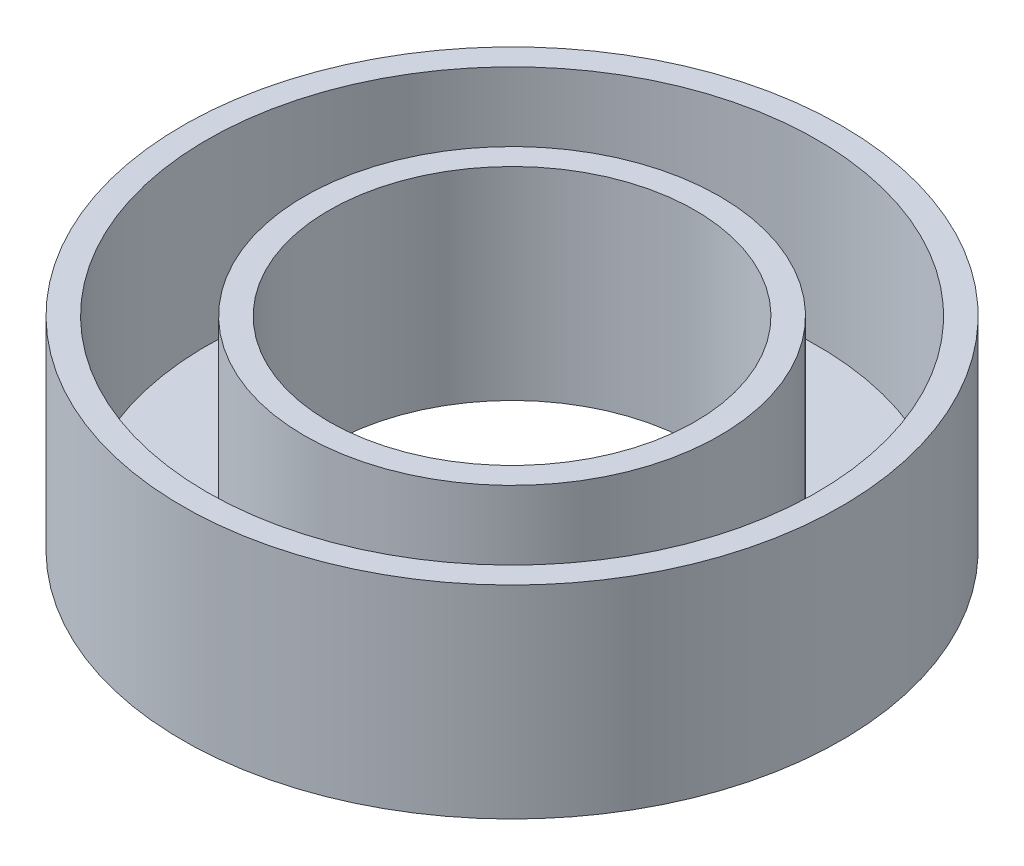
SolidWorks part; units mm, degrees
material "VITON"
ref_plane "Front Plane" through (0, 0, 0) normal (0, 0, 1) x (1, 0, 0)
ref_plane "Top Plane" through (0, 0, 0) normal (0, 1, 0) x (1, 0, 0)
ref_plane "Right Plane" through (0, 0, 0) normal (1, 0, 0) x (0, 0, -1)
sketch "Sketch1" plane through (0, 0, 0) normal (0, 1, 0) x (1, 0, 0)
  circle A0 centre (0, 0) radius 13.5
  dimension "D1" = 27
extrude "main extrusion" add sketch "Sketch1" along normal blind 8.3 contours A0
sketch "Sketch2" plane through (0, 8.3, 0) normal (0, 1, 0) x (1, 0, 0)
  circle A0 centre (0, 0) radius 7.5
  dimension "D1" = 15
extrude "ID bore" cut sketch "Sketch2" against normal blind 20
sketch "Sketch3" plane through (0, 8.3, 0) normal (0, 1, 0) x (1, 0, 0)
  circle A0 centre (0, 0) radius 12.5
  circle A1 centre (0, 0) radius 8.5
  dimension "D1" = 17
  dimension "D2" = 25
extrude "seal recess" cut sketch "Sketch3" against normal blind 7.3
equation "\"D1@Sketch1\" = \"big seal OD\""
equation "\"D1@main extrusion\"=\"big seal depth\""
equation "\"D1@Sketch2\" = \"big seal ID\""
equation "\"motor mount pattern diameter\"= 30mm"
equation "\"D2@Sketch3\" = \"big seal OD\" - 2mm"
equation "\"D1@Sketch3\" = \"big seal ID\" + 2mm"
equation "\"D1@seal recess\" = \"big seal depth\" - 1mm"
equation "\"bearing OD\"= 30mm"
equation "\"bearing outer race thickness\"= 1mm"
equation "\"bearing ID\"= 10mm"
equation "\"bearing depth\"= 9mm"
equation "\"bearing inner race thickness\"= 1mm"
equation "\"small seal OD\"= 20mm"
equation "\"small seal ID\"= 8mm"
equation "\"small seal depth\"= 8.3mm"
equation "\"big seal OD\"= 27mm"
equation "\"big seal ID\"= 15mm"
equation "\"big seal depth\"= 8.3mm"
